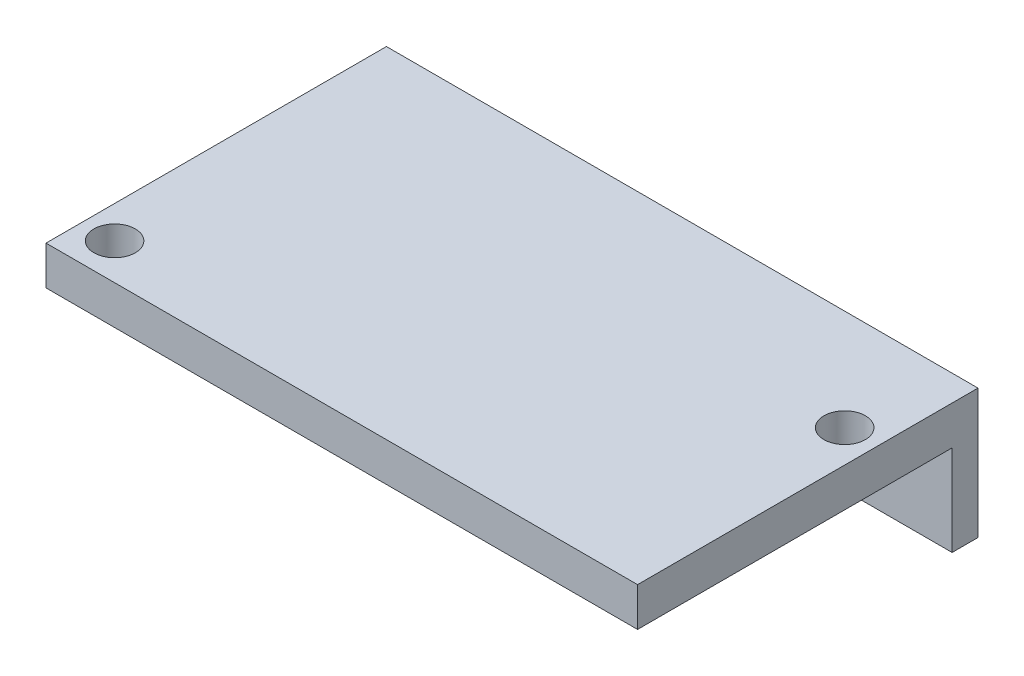
SolidWorks part; units mm, degrees
ref_plane "Front Plane" through (0, 0, 0) normal (0, 0, 1) x (1, 0, 0)
ref_plane "Top Plane" through (0, 0, 0) normal (0, 1, 0) x (1, 0, 0)
ref_plane "Right Plane" through (0, 0, 0) normal (1, 0, 0) x (0, 0, -1)
sketch "Çizim1" plane through (0, 0, 0) normal (0, 1, 0) x (1, 0, 0)
  line L1 (-22.85, -12.15) -> (22.85, -12.15)
  line L2 (-22.85, -12.15) -> (-22.85, 12.15)
  line L3 (-22.85, 12.15) -> (22.85, 12.15)
  line L4 (22.85, -12.15) -> (22.85, 12.15)
  line L5 (-22.85, -12.15) -> (22.85, 12.15) construction
  line L6 (-22.85, 12.15) -> (22.85, -12.15) construction
  point P0 (0, 0)
  dimension "D1" = 45.7
  dimension "D2" = 24.3
extrude "Yükseklik-Ekstrüzyon1" add sketch "Çizim1" along normal blind 3
sketch "Çizim2" plane through (0, 3, 0) normal (0, 1, 0) x (1, 0, 0)
  line L0 (-22.85, 12.15) -> (-22.85, -12.15) construction
  line L1 (-22.85, -12.15) -> (22.85, -12.15) construction
  line L2 (22.85, 12.15) -> (-22.85, 12.15) construction
  line L3 (22.85, -12.15) -> (22.85, 12.15) construction
  circle A0 centre (-20.35, -9.35) radius 1.6
  circle A1 centre (20.35, 6.35) radius 1.6
  dimension "D1" = 3.2
  dimension "D2" = 3.2
  dimension "D3" = 43.2
  dimension "D5" = 21.5
  dimension "D6" = 43.2
  dimension "D4" = 18.5
extrude "Kes-Ekstrüzyon1" cut sketch "Çizim2" against normal blind 21.8
sketch "Çizim4" plane through (0, 3, 0) normal (0, 1, 0) x (1, 0, 0)
  line L0 (-22.85, -12.15) -> (22.85, -12.15) construction
  line L1 (-22.85, 14.15) -> (22.85, 14.15)
  line L2 (-22.85, 14.15) -> (-22.85, 12.15)
  line L3 (-22.85, 12.15) -> (22.85, 12.15)
  line L4 (22.85, 14.15) -> (22.85, 12.15)
  line L5 (-22.85, 14.15) -> (22.85, 12.15) construction
  line L6 (-22.85, 12.15) -> (22.85, 14.15) construction
  line L8 (-22.85, 12.15) -> (-22.85, -12.15) construction
  point P0 (0, 13.15)
  dimension "D1" = 45.7
  dimension "D2" = 2
  dimension "D3" = 24.3
  dimension "D4" = 0
extrude "Yükseklik-Ekstrüzyon2" add sketch "Çizim4" against normal blind 10
sketch "Çizim5" plane through (0, 0, -14.15) normal (0, 0, -1) x (-1, 0, 0)
  line L0 (22.85, -7) -> (22.85, 3) construction
  line L1 (-22.85, -7) -> (-22.85, 3) construction
  line L2 (-22.85, 3) -> (22.85, 3) construction
  circle A0 centre (-12.85, -4) radius 1.6
  circle A1 centre (12.85, -4) radius 1.6
  dimension "D1" = 3.2
  dimension "D2" = 3.2
  dimension "D3" = 10
  dimension "D5" = 7
  dimension "D6" = 7
  dimension "D4" = 10
extrude "Kes-Ekstrüzyon2" cut sketch "Çizim5" against normal blind 4
